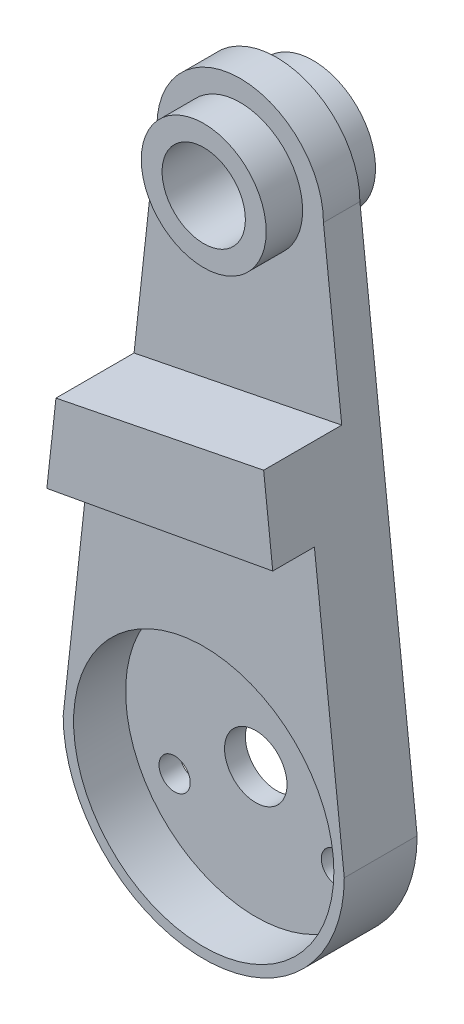
SolidWorks part; units mm, degrees
ref_plane "Plan de face" through (0, 0, 0) normal (0, 0, 1) x (1, 0, 0)
ref_plane "Plan de dessus" through (0, 0, 0) normal (0, 1, 0) x (1, 0, 0)
ref_plane "Plan de droite" through (0, 0, 0) normal (1, 0, 0) x (0, 0, -1)
sketch "Esquisse1" plane through (0, 0, 0) normal (0, 0, 1) x (1, 0, 0)
  line L0 (-16.3093, 0) -> (24.5372, 0) construction
  line L1 (8, 0) -> (13.5, -50)
  line L2 (-8, 0) -> (-13.5, -50)
  line L3 (-13.5, -50) -> (13.5, -50) construction
  line L4 (0, 0) -> (0, -50) construction
  arc A0 (-8, 0) -> (8, 0) centre (0, 0) cw
  arc A1 (-13.5, -50) -> (13.5, -50) centre (0, -50) ccw
  dimension "D1" = 8
  dimension "D2" = 13.5
  dimension "D3" = 50
extrude "Boss.-Extru.1" add sketch "Esquisse1" along normal blind 7
sketch "Esquisse2" plane through (0, 0, 7) normal (0, 0, 1) x (1, 0, 0)
  line L0 (0, 0) -> (0, -63.5) construction
  line L1 (13.5, -50) -> (-13.5, -50) construction
  circle A0 centre (0, -50) radius 3
  arc A1 (-13.5, -50) -> (13.5, -50) centre (0, -50) ccw construction
  dimension "D1" = 6
extrude "Enlèv. mat.-Extru.1" cut sketch "Esquisse2" against normal blind 7
sketch "Esquisse3" plane through (0, 0, 7) normal (0, 0, 1) x (1, 0, 0)
  line L0 (0, -50) -> (0, 0) construction
  line L1 (0, -50) -> (-7.7942, -54.5) construction
  line L2 (0, -50) -> (7.7942, -54.5) construction
  circle A0 centre (0, -41) radius 1.5
  circle A1 centre (-7.7942, -54.5) radius 1.5
  circle A2 centre (7.7942, -54.5) radius 1.5
  dimension "D1" = 3
  dimension "D2" = 3
  dimension "D3" = 3
  dimension "D4" = 9
  dimension "D5" = 9
  dimension "D6" = 9
  dimension "D7" = 120
  dimension "D8" = 120
extrude "Enlèv. mat.-Extru.2" cut sketch "Esquisse3" against normal blind 7
ref_plane "Plan1" through (0, 10, 0) normal (0, 1, 0) x (1, 0, 0)
sketch "Esquisse10" plane through (0, 10, 0) normal (0, 1, 0) x (1, 0, 0)
  line L0 (-13.5, -7) -> (-13.5, 0) construction
  line L1 (13.5, -7) -> (-13.5, -7)
  line L2 (13.5, -7) -> (13.5, -3.5)
  line L3 (13.5, -3.5) -> (-13.5, -3.5)
  line L4 (-13.5, -7) -> (-13.5, -3.5)
  line L5 (-8, -7) -> (-13.5, -7) construction
sketch "Esquisse5" plane through (0, 0, 7) normal (0, 0, 1) x (1, 0, 0)
  circle A0 centre (0, -50) radius 12.5
  dimension "D1" = 25
extrude "Enlèv. mat.-Extru.5" cut sketch "Esquisse5" against normal blind 5
extrude "Enlèv. mat.-Extru.6" cut sketch "Esquisse10" against normal blind 20
sketch "Esquisse12" plane through (0, 0, 3.5) normal (0, 0, 1) x (1, 0, 0)
  circle A0 centre (0, 0) radius 6
  dimension "D1" = 12
extrude "Boss.-Extru.3" add sketch "Esquisse12" along normal blind 3.5
sketch "Esquisse13" plane through (0, 0, 7) normal (0, 0, 1) x (1, 0, 0)
  circle A0 centre (0, 0) radius 4
  dimension "D1" = 8
extrude "Enlèv. mat.-Extru.7" cut sketch "Esquisse13" against normal through all
sketch "Esquisse14" plane through (0, 0, 7) normal (0, 0, 1) x (1, 0, 0)
  line L2 (-9.1, -10) -> (-10.1934, -19.94)
  line L3 (-9.1, -10) -> (-13.5, -50) construction
  line L5 (-9.1, -10) -> (9.1, -10)
  line L6 (-9.1, -10) -> (9.1, -10) construction
  line L9 (13.5, -50) -> (9.1, -10) construction
  line L14 (9.1, -10) -> (9.756, -15.964)
  line L15 (-10.1934, -19.94) -> (9.756, -15.964)
extrude "Enlèv. mat.-Extru.8" cut sketch "Esquisse14" against normal blind 3.5
sketch "Esquisse15" plane through (0, 0, 7) normal (0, 0, 1) x (1, 0, 0)
  line L0 (-10.1934, -19.94) -> (9.756, -15.964)
  line L1 (9.756, -15.964) -> (10.6308, -23.9161)
  line L2 (13.5, -50) -> (9.756, -15.964) construction
  line L3 (-10.1934, -19.94) -> (-11.0681, -27.8921)
  line L4 (-10.1934, -19.94) -> (-13.5, -50) construction
  line L5 (-11.0681, -27.8921) -> (10.6308, -23.9161)
extrude "Boss.-Extru.4" add sketch "Esquisse15" along normal blind 4
sketch "Esquisse16" plane through (0, 0, 0) normal (0, 0, -1) x (-1, 0, 0)
  circle A0 centre (0, 0) radius 6
  circle A1 centre (0, 0) radius 4
extrude "Boss.-Extru.5" add sketch "Esquisse16" along normal blind 3.5
